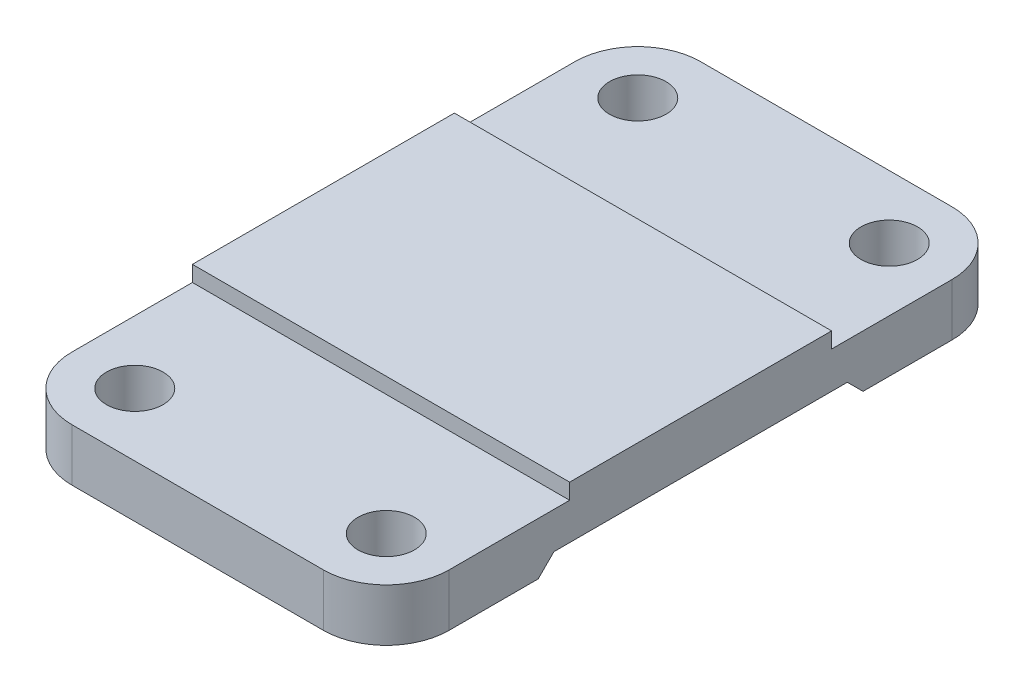
SolidWorks part; units mm, degrees
ref_plane "Front Plane" through (0, 0, 0) normal (0, 0, 1) x (1, 0, 0)
ref_plane "Top Plane" through (0, 0, 0) normal (0, 1, 0) x (1, 0, 0)
ref_plane "Right Plane" through (0, 0, 0) normal (1, 0, 0) x (0, 0, -1)
sketch "Sketch1" plane through (0, 0, 0) normal (1, 0, 0) x (0, 0, -1)
  line L0 (-28, 3) -> (-31, 0)
  line L1 (-31, 0) -> (-60, 0)
  line L2 (-60, 0) -> (-60, 10)
  line L3 (-60, 10) -> (-25, 10)
  line L4 (-25, 10) -> (-25, 13)
  line L5 (0, 55) -> (0, -55) construction
  line L6 (25, 10) -> (25, 13)
  line L7 (60, 10) -> (25, 10)
  line L8 (60, 0) -> (60, 10)
  line L9 (31, 0) -> (60, 0)
  line L10 (28, 3) -> (31, 0)
  line L11 (-25, 13) -> (25, 13)
  line L12 (-28, 3) -> (28, 3)
  dimension "D1" = 62
  dimension "D2" = 50
  dimension "D3" = 3
  dimension "D4" = 135
  dimension "D5" = 120
  dimension "D6" = 10
  dimension "D7" = 3
extrude "Boss-Extrude1" add sketch "Sketch1" along normal mid plane 72
fillet "Fillet1" radius 12 4 edges at (-36, 5, -60) (36, 5, -60) (-36, 5, 60) (36, 5, 60)
hole_wizard "M12x1.25 Tapped Hole1" positions "Sketch2" profile "Sketch3" tap size "M12x1.25" standard "ANSI Metric" end condition up to next
sketch "Sketch2" plane through (0, 10, 0) normal (0, 1, 0) x (1, 0, 0)
  point P0 (24, -48)
  point P3 (-24, -48)
  point P6 (24, 48)
  point P9 (-24, 48)
sketch "Sketch3" plane through (24, 10, 48) normal (1, 0, 0) x (0, 0, 1)
  line L0 (0, 0) -> (0, 10)
  line L1 (0, 10) -> (5.4, 10)
  line L2 (5.4, 10) -> (5.4, 0)
  line L5 (5.4, 0) -> (0, 0)
  line L11 (0, -6.35) -> (0, 107.95) construction
  dimension "Thru Tap Drill Dia." = 10.8
  dimension "Thru Tap Drill Depth" = 10
cosmetic thread "Hole Thread1" parameters "D2"=12
cosmetic thread "Hole Thread2" parameters "D2"=12
cosmetic thread "Hole Thread3" parameters "D2"=12
cosmetic thread "Hole Thread4" parameters "D2"=12
